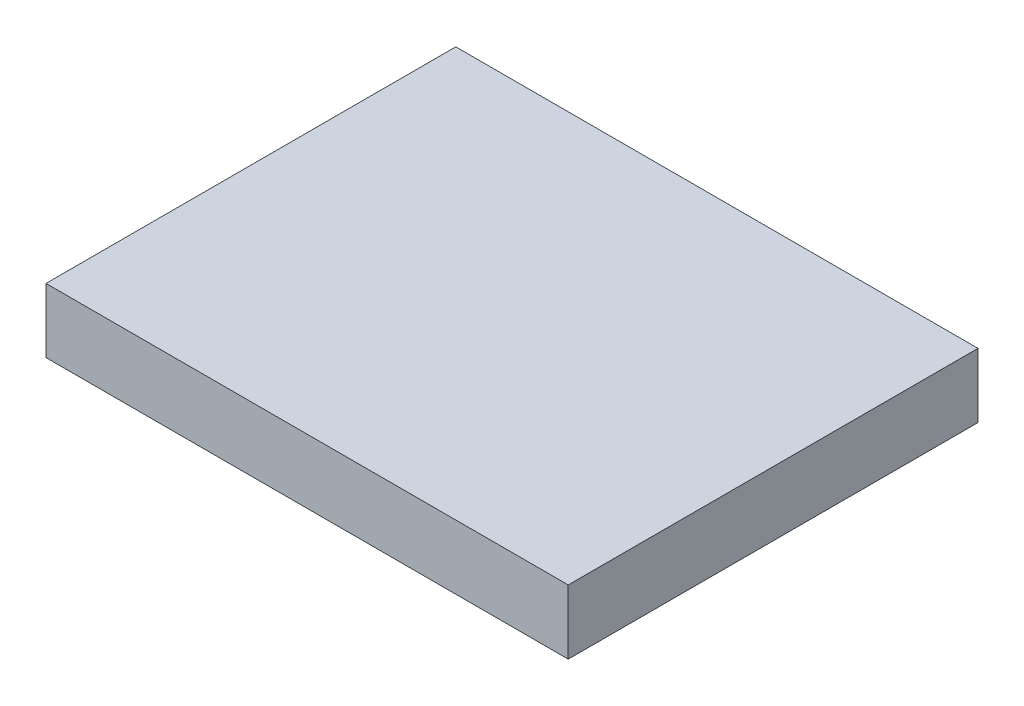
SolidWorks part; units mm, degrees
ref_plane "Front Plane" through (0, 0, 0) normal (0, 0, 1) x (1, 0, 0)
ref_plane "Top Plane" through (0, 0, 0) normal (0, 1, 0) x (1, 0, 0)
ref_plane "Right Plane" through (0, 0, 0) normal (1, 0, 0) x (0, 0, -1)
sketch "Sketch1" plane through (0, 0, 0) normal (0, 1, 0) x (1, 0, 0)
  line L0 (0, 0) -> (0, 51)
  line L1 (0, 51) -> (65, 51)
  line L2 (65, 51) -> (65, 0)
  line L3 (65, 0) -> (0, 0)
  dimension "D1" = 51
  dimension "D2" = 65
extrude "Boss-Extrude1" add sketch "Sketch1" along normal blind 8
